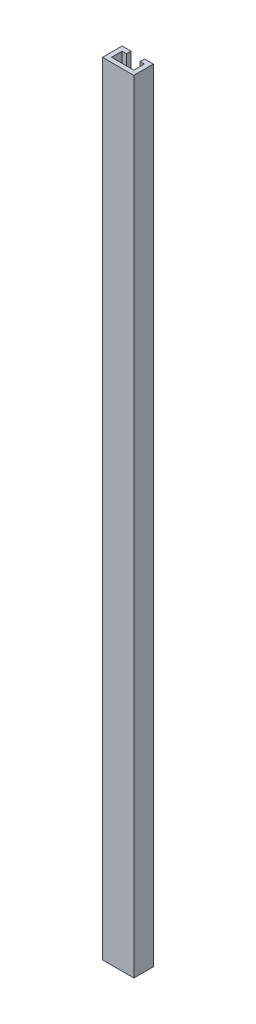
SolidWorks part; units mm, degrees
ref_plane "前视基准面" through (0, 0, 0) normal (0, 0, 1) x (1, 0, 0)
ref_plane "上视基准面" through (0, 0, 0) normal (0, 1, 0) x (1, 0, 0)
ref_plane "右视基准面" through (0, 0, 0) normal (1, 0, 0) x (0, 0, -1)
sketch "草图1" plane through (0, 0, 0) normal (0, 1, 0) x (1, 0, 0)
  line L0 (0, -5) -> (8, -5)
  line L1 (8, -5) -> (8, 0)
  line L2 (8, 0) -> (5.75, 0)
  line L3 (5.75, 0) -> (5.75, -1.15)
  line L4 (5.75, -1.15) -> (6.85, -1.15)
  line L5 (6.85, -1.15) -> (6.85, -3.85)
  line L6 (6.85, -3.85) -> (1.15, -3.85)
  line L7 (1.15, -3.85) -> (1.15, -1.15)
  line L8 (1.15, -1.15) -> (2.25, -1.15)
  line L9 (2.25, -1.15) -> (2.25, 0)
  line L10 (2.25, 0) -> (0, 0)
  line L11 (0, 0) -> (0, -5)
  line L12 (4, -3.85) -> (4, -5) construction
  line L13 (2.25, 0) -> (5.75, 0) construction
  line L14 (4, 0) -> (4, -3.85) construction
  dimension "D1" = 5
  dimension "D2" = 8
  dimension "D3" = 1.15
  dimension "D4" = 1.15
  dimension "D5" = 1.15
  dimension "D6" = 3.5
  dimension "D7" = 5.7
extrude "凸台-拉伸1" add sketch "草图1" along normal blind 200
